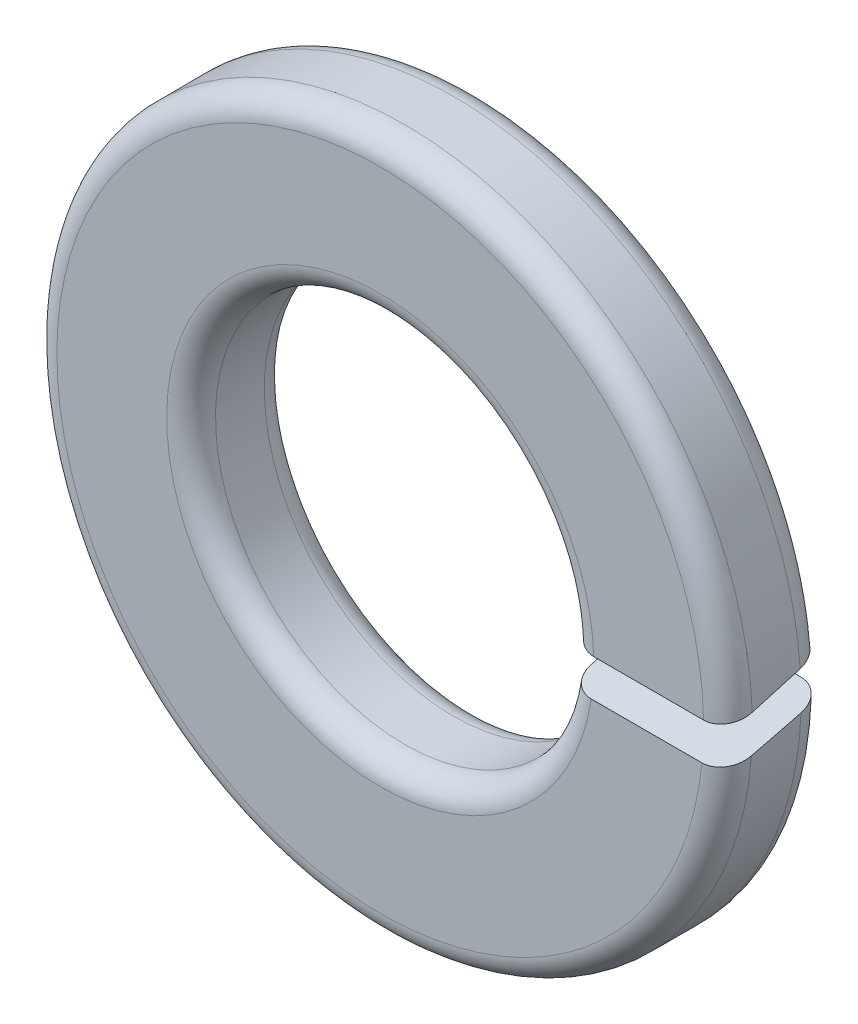
SolidWorks part; units mm, degrees
ref_plane "Přední rovina" through (0, 0, 0) normal (0, 0, 1) x (1, 0, 0)
ref_plane "Vrchní rovina" through (0, 0, 0) normal (0, 1, 0) x (1, 0, 0)
ref_plane "Pravá rovina" through (0, 0, 0) normal (1, 0, 0) x (0, 0, -1)
sketch "Skica1" plane through (0, 0, 0) normal (0, 0, 1) x (1, 0, 0)
  circle A0 centre (0, 0) radius 1.55
  circle A1 centre (0, 0) radius 2.85
  dimension "d1" = 3.1
  dimension "d2" = 5.7
extrude "Vysunout1" add sketch "Skica1" along normal blind 0.8
fillet "Zaoblit1" radius 0.2 4 edges at (2.85, 0, 0) (2.85, 0, 0.8) (1.55, 0, 0) (1.55, 0, 0.8)
sketch "Skica2" plane through (0, 0, 0) normal (1, 0, 0) x (0, 0, -1)
  line L0 (0, 0) -> (-0.8, 0) construction
  line L1 (-0.8, 2.85) -> (-0.8, -2.85) construction
  line L2 (0, -0.0481) -> (-0.8, -0.2625)
  line L3 (0, -2.85) -> (0, 2.85) construction
  line L4 (0, 0.2625) -> (-0.8, 0.0481)
  line L5 (0, -0.0481) -> (0, 0.2625)
  line L6 (-0.8, -0.2625) -> (-0.8, 0.0481)
  line L7 (0, 0.2625) -> (0, 0) construction
  line L8 (-0.8, 0) -> (-0.8, -0.2625) construction
  dimension "D1" = 75
  dimension "D2" = 0.3
extrude "Odebrat vysunutím1" cut sketch "Skica2" along normal through all
equation "\"D2@Skica2\" = \"R@Zaoblit1\" * 1.5"
